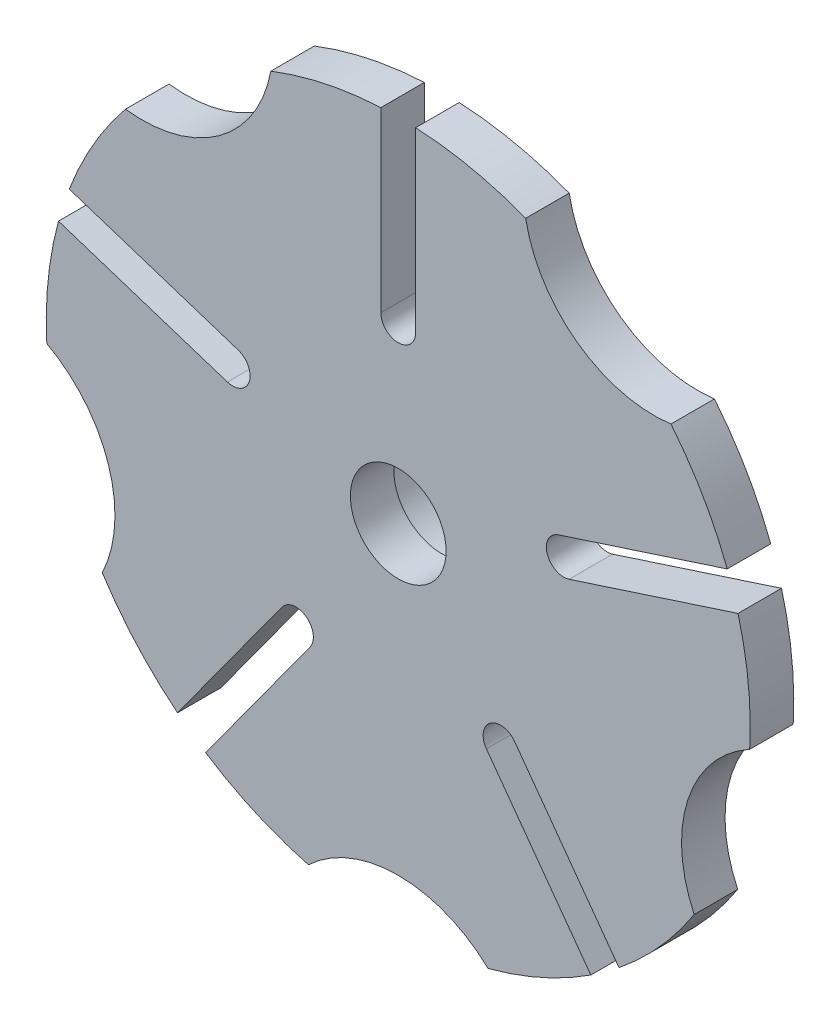
SolidWorks part; units mm, degrees
ref_plane "Ön Düzlem" through (0, 0, 0) normal (0, 0, 1) x (1, 0, 0)
ref_plane "Üst Düzlem" through (0, 0, 0) normal (0, 1, 0) x (1, 0, 0)
ref_plane "Sağ Düzlem" through (0, 0, 0) normal (1, 0, 0) x (0, 0, -1)
sketch "Sketch1" plane through (0, 0, 0) normal (0, 0, 1) x (1, 0, 0)
  line L0 (-109.1348, 0) -> (109.1348, 0) construction
  line L1 (-91.3643, -100) -> (91.3643, -100) construction
  line L2 (0, 0) -> (0, -176.3006) construction
  line L3 (0, -100) -> (47.5528, -65.4508) construction
  line L4 (47.5528, -65.4508) -> (0, 0) construction
  line L5 (0, -100) -> (55.9017, -118.1636) construction
  line L6 (44.5378, -55.9162) -> (0, -70)
  line L7 (55.6891, -71.2647) -> (28.5317, -109.2705)
  line L8 (26.7475, -30.0095) -> (50.7307, -63.0197)
  line L9 (20.2753, -34.7118) -> (44.2586, -67.7219)
  circle A2 centre (47.5528, -65.4508) radius 4
  circle A3 centre (0, -100) radius 58.7785 construction
  circle A4 centre (47.5528, -65.4508) radius 10
  circle A5 centre (0, 0) radius 80.9017
  circle A6 centre (0, -100) radius 30
  circle A7 centre (23.5114, -32.3607) radius 4
  circle A8 centre (0, -100) radius 58.778 construction
  circle A9 centre (0, 0) radius 40 construction
  arc A10 (28.5317, -109.2705) -> (0, -70) centre (76.7005, -44.2738) cw
  point P6 (0, -100)
  dimension "D4" = 8
  dimension "D6" = 20
  dimension "D7" = 60
  dimension "D8" = 117.556
  dimension "D9" = 80
  dimension "D10" = 80.9
  dimension "D1" = 100
  dimension "D2" = 36
  dimension "D3" = 54
  dimension "D5" = 252
sketch "Sketch2" plane through (0, 0, 0) normal (0, 0, 1) x (1, 0, 0)
  line L0 (26.7475, -30.0095) -> (50.7307, -63.0197) construction
  line L1 (20.2753, -34.7118) -> (44.2586, -67.7219) construction
  line L2 (26.7475, -30.0095) -> (50.7307, -63.0197)
  line L3 (20.2753, -34.7118) -> (44.2586, -67.7219)
  line L4 (-26.7475, -30.0095) -> (-50.7307, -63.0197)
  line L5 (-20.2753, -34.7118) -> (-44.2586, -67.7219)
  line L6 (-36.8062, 16.1649) -> (-75.6119, 28.7737)
  line L7 (-39.2783, 8.5565) -> (-78.0841, 21.1652)
  line L8 (4, 40) -> (4, 80.8028)
  line L9 (-4, 40) -> (-4, 80.8028)
  line L10 (39.2783, 8.5565) -> (78.0841, 21.1652)
  line L11 (36.8062, 16.1649) -> (75.6119, 28.7737)
  circle A0 centre (23.5114, -32.3607) radius 4 construction
  circle A1 centre (0, -100) radius 30 construction
  circle A2 centre (0, 0) radius 80.9017 construction
  arc A3 (26.7475, -30.0095) -> (20.2753, -34.7118) centre (23.5114, -32.3607) ccw
  arc A4 (20.6366, -78.2254) -> (-20.6366, -78.2254) centre (0, -100) ccw
  arc A5 (20.6366, -78.2254) -> (44.2586, -67.7219) centre (0, 0) ccw
  arc A6 (-68.0198, -43.7995) -> (-80.7738, -4.5464) centre (-95.1057, -30.9017) ccw
  arc A7 (-20.2753, -34.7118) -> (-26.7475, -30.0095) centre (-23.5114, -32.3607) ccw
  arc A8 (-62.6751, 51.1558) -> (-29.2844, 75.4156) centre (-58.7785, 80.9017) ccw
  arc A9 (-39.2783, 8.5565) -> (-36.8062, 16.1649) centre (-38.0423, 12.3607) ccw
  arc A10 (29.2844, 75.4156) -> (62.6751, 51.1558) centre (58.7785, 80.9017) ccw
  arc A11 (-4, 40) -> (4, 40) centre (0, 40) ccw
  arc A12 (80.7738, -4.5464) -> (68.0198, -43.7995) centre (95.1057, -30.9017) ccw
  arc A13 (36.8062, 16.1649) -> (39.2783, 8.5565) centre (38.0423, 12.3607) ccw
  circle A14 centre (0, 0) radius 40 construction
  arc A15 (-68.0198, -43.7995) -> (-50.7307, -63.0197) centre (0, 0) ccw
  arc A16 (-62.6751, 51.1558) -> (-75.6119, 28.7737) centre (0, 0) ccw
  arc A17 (29.2844, 75.4156) -> (4, 80.8028) centre (0, 0) ccw
  arc A18 (80.7738, -4.5464) -> (78.0841, 21.1652) centre (0, 0) ccw
  arc A19 (50.7307, -63.0197) -> (68.0198, -43.7995) centre (0, 0) ccw
  arc A20 (-44.2586, -67.7219) -> (-20.6366, -78.2254) centre (0, 0) ccw
  arc A21 (-78.0841, 21.1652) -> (-80.7738, -4.5464) centre (0, 0) ccw
  arc A22 (-4, 80.8028) -> (-29.2844, 75.4156) centre (0, 0) ccw
  arc A23 (75.6119, 28.7737) -> (62.6751, 51.1558) centre (0, 0) ccw
  circle A24 centre (0, 0) radius 11
  dimension "D2" = 22
  dimension "D1" = 5
extrude "Boss-Extrude1" add sketch "Sketch2" along normal blind 10
sketch "Sketch4" plane through (0, 0, 0) normal (0, 0, -1) x (-1, 0, 0)
  line L0 (109.1348, 0) -> (-109.1348, 0) construction
  circle A0 centre (0, 0) radius 19
  circle A4 centre (0, 0) radius 15
  dimension "D1" = 38
  dimension "D2" = 30
extrude "Boss-Extrude2" add sketch "Sketch4" along normal blind 10
